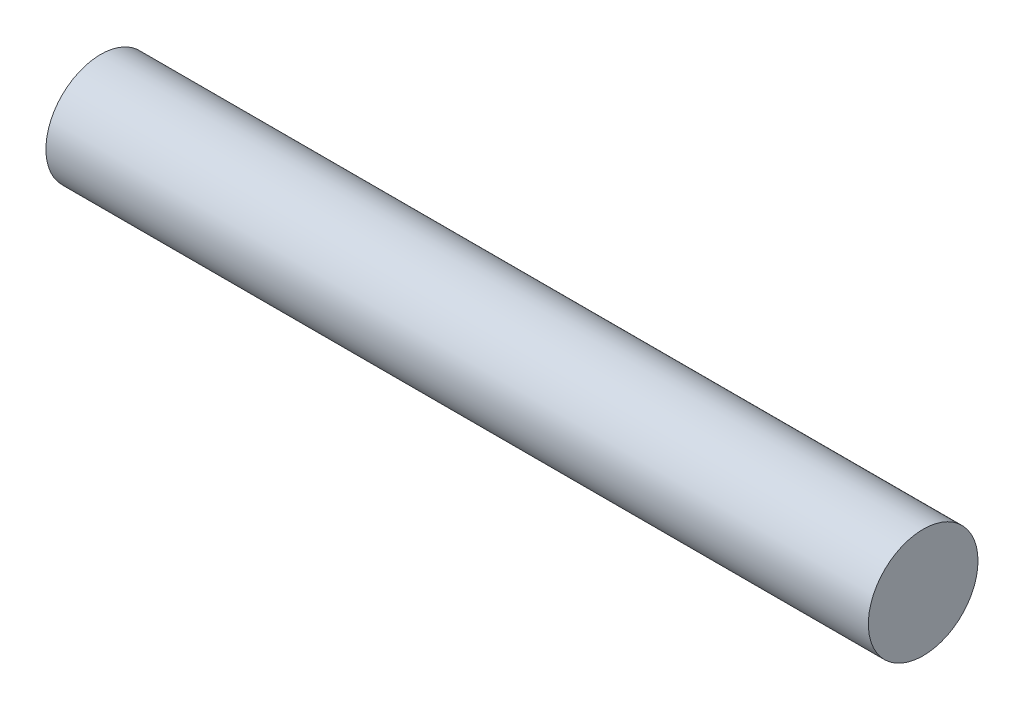
SolidWorks part; units mm, degrees
ref_plane "Front Plane" through (0, 0, 0) normal (0, 0, 1) x (1, 0, 0)
ref_plane "Top Plane" through (0, 0, 0) normal (0, 1, 0) x (1, 0, 0)
ref_plane "Right Plane" through (0, 0, 0) normal (1, 0, 0) x (0, 0, -1)
sketch "Sketch1" plane through (0, 0, 0) normal (1, 0, 0) x (0, 0, -1)
  circle A0 centre (0, 0) radius 2
  dimension "D1" = 4
extrude "Boss-Extrude1" add sketch "Sketch1" along normal blind 30
